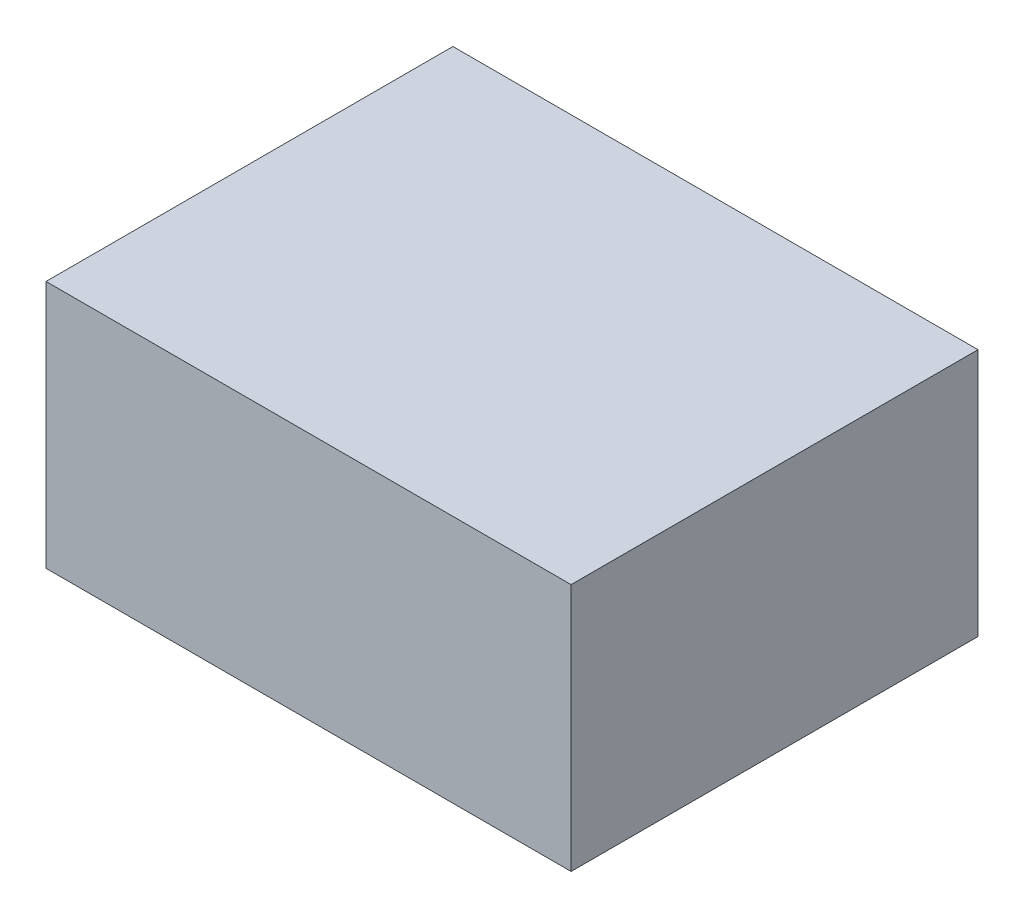
SolidWorks part; units mm, degrees
ref_plane "前视基准面" through (0, 0, 0) normal (0, 0, 1) x (1, 0, 0)
ref_plane "上视基准面" through (0, 0, 0) normal (0, 1, 0) x (1, 0, 0)
ref_plane "右视基准面" through (0, 0, 0) normal (1, 0, 0) x (0, 0, -1)
sketch "草图1" plane through (0, 0, 0) normal (0, 0, 1) x (1, 0, 0)
  line L1 (195.5, 92.5) -> (-195.5, 92.5)
  line L2 (195.5, 92.5) -> (195.5, -92.5)
  line L3 (195.5, -92.5) -> (-195.5, -92.5)
  line L4 (-195.5, 92.5) -> (-195.5, -92.5)
  line L5 (195.5, 92.5) -> (-195.5, -92.5) construction
  line L6 (195.5, -92.5) -> (-195.5, 92.5) construction
  point P0 (0, 0)
extrude "凸台-拉伸1" add sketch "草图1" along normal blind 303
